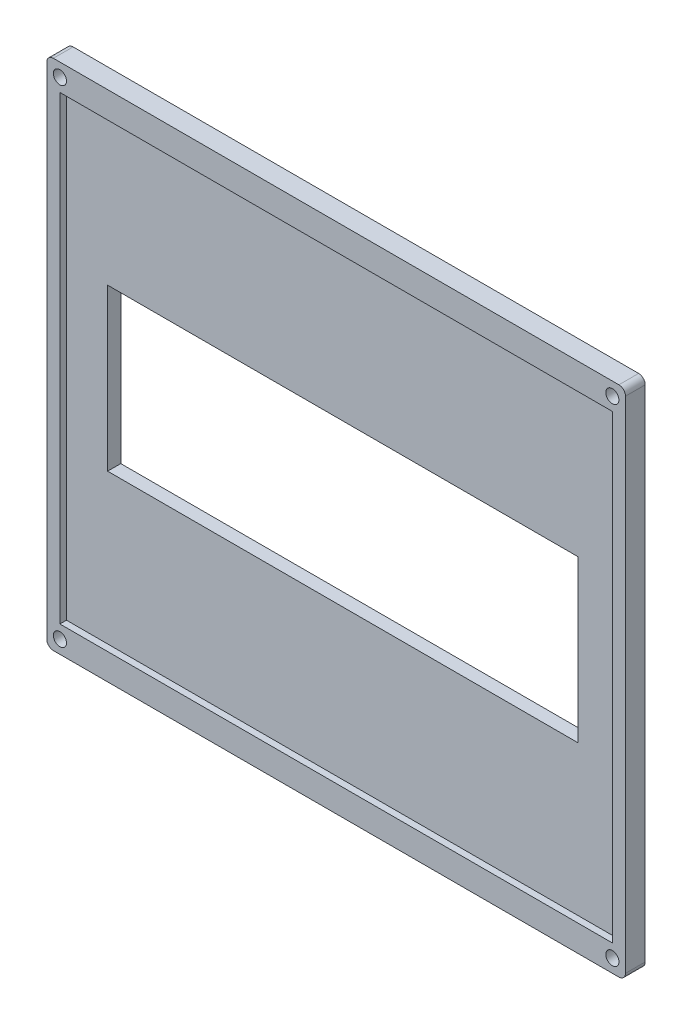
SolidWorks part; units mm, degrees
ref_plane "Front Plane" through (0, 0, 0) normal (0, 0, 1) x (1, 0, 0)
ref_plane "Top Plane" through (0, 0, 0) normal (0, 1, 0) x (1, 0, 0)
ref_plane "Right Plane" through (0, 0, 0) normal (1, 0, 0) x (0, 0, -1)
sketch "Sketch2" plane through (0, 0, 0) normal (0, 0, 1) x (1, 0, 0)
  line L1 (-44, 39) -> (44, 39)
  line L2 (-44, 39) -> (-44, -39)
  line L3 (-44, -39) -> (44, -39)
  line L4 (44, 39) -> (44, -39)
  line L5 (-44, 39) -> (44, -39) construction
  line L6 (-44, -39) -> (44, 39) construction
  point P0 (0, 0)
  dimension "D1" = 88
  dimension "D2" = 78
extrude "Boss-Extrude1" add sketch "Sketch2" along normal blind 3 contours L2 L1 L4 L3
sketch "Sketch3" plane through (0, 0, 3) normal (0, 0, 1) x (1, 0, 0)
  line L1 (-42, 35) -> (42, 35)
  line L2 (-42, 35) -> (-42, -35)
  line L3 (-42, -35) -> (42, -35)
  line L4 (42, 35) -> (42, -35)
  line L5 (-42, 35) -> (42, -35) construction
  line L6 (-42, -35) -> (42, 35) construction
  point P0 (0, 0)
  dimension "D1" = 84
  dimension "D2" = 70
extrude "Cut-Extrude1" cut sketch "Sketch3" against normal blind 1
sketch "Sketch4" plane through (0, 0, 3) normal (0, 0, 1) x (1, 0, 0)
  line L0 (-42, 35) -> (-42, 39) construction
  line L1 (-44, 39) -> (44, 39) construction
  line L2 (42, 35) -> (42, 39) construction
  line L3 (-42, -35) -> (-42, -39) construction
  line L4 (-44, -39) -> (44, -39) construction
  line L5 (42, -35) -> (42, -39) construction
  circle A0 centre (-42, 37) radius 1
  circle A1 centre (42, 37) radius 1
  circle A2 centre (-42, -37) radius 1
  circle A3 centre (42, -37) radius 1
extrude "Cut-Extrude2" cut sketch "Sketch4" against normal blind 3
fillet "Fillet1" radius 1 4 edges at (44, -39, 1.5) (-44, -39, 1.5) (44, 39, 1.5) (-44, 39, 1.5)
sketch "Sketch5" plane through (0, 0, 2) normal (0, 0, 1) x (1, 0, 0)
  line L1 (-35.75, 12.25) -> (35.75, 12.25)
  line L2 (-35.75, 12.25) -> (-35.75, -12.25)
  line L3 (-35.75, -12.25) -> (35.75, -12.25)
  line L4 (35.75, 12.25) -> (35.75, -12.25)
  line L5 (-35.75, 12.25) -> (35.75, -12.25) construction
  line L6 (-35.75, -12.25) -> (35.75, 12.25) construction
  point P0 (0, 0)
  dimension "D1" = 71.5
  dimension "D2" = 24.5
extrude "Cut-Extrude3" cut sketch "Sketch5" against normal blind 3
